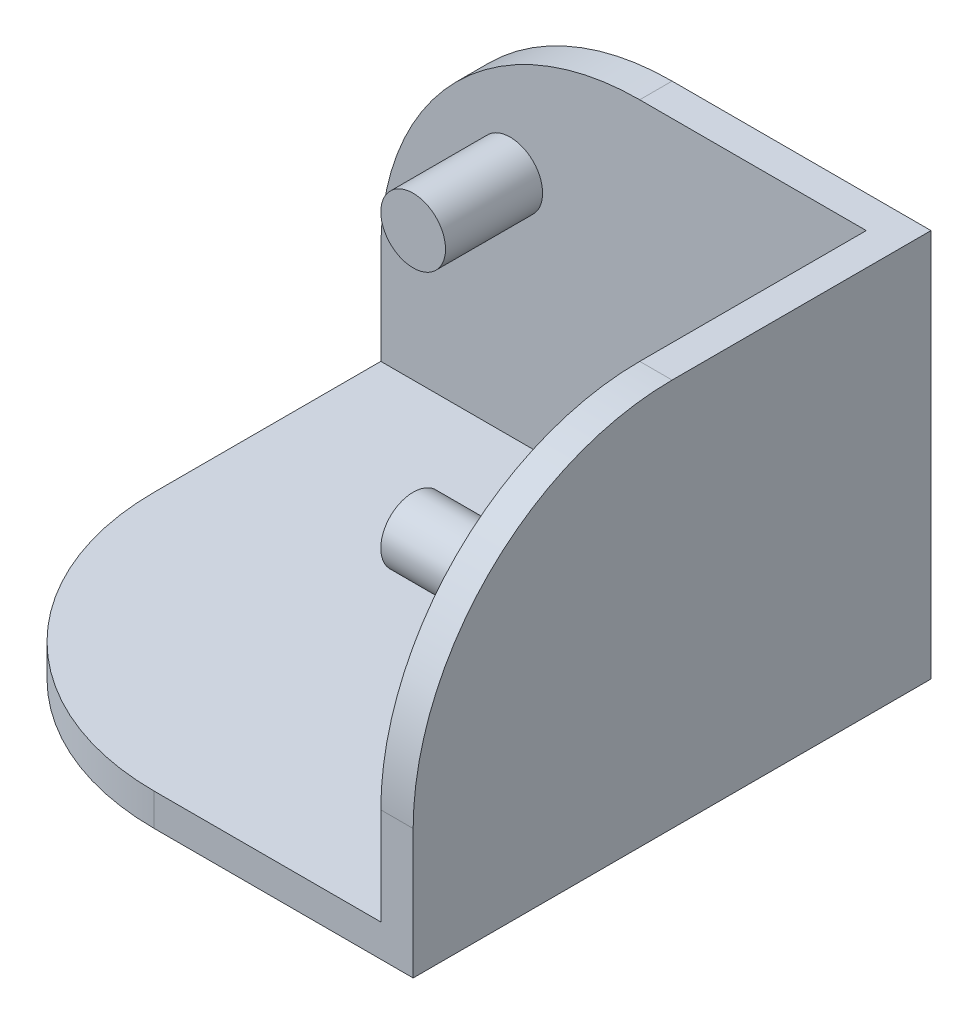
SolidWorks part; units mm, degrees
ref_plane "Front Plane" through (0, 0, 0) normal (0, 0, 1) x (1, 0, 0)
ref_plane "Top Plane" through (0, 0, 0) normal (0, 1, 0) x (1, 0, 0)
ref_plane "Right Plane" through (0, 0, 0) normal (1, 0, 0) x (0, 0, -1)
sketch "Sketch1" plane through (0, 0, 0) normal (0, 1, 0) x (1, 0, 0)
  line L1 (-40, 40) -> (40, 40)
  line L2 (-40, 40) -> (-40, -40)
  line L3 (-40, -40) -> (40, -40)
  line L4 (40, 40) -> (40, -40)
  line L5 (-40, 40) -> (40, -40) construction
  line L6 (-40, -40) -> (40, 40) construction
  point P0 (0, 0)
  dimension "D1" = 80
extrude "Boss-Extrude1" add sketch "Sketch1" along normal blind 5
sketch "Sketch3" plane through (0, 5, 0) normal (0, 1, 0) x (1, 0, 0)
  line L0 (-40, 40) -> (40, 40)
  line L1 (40, 40) -> (40, -40)
extrude "Extrude-Thin1" add sketch "Sketch3" along normal blind 55 thin
fillet "Fillet1" radius 40 3 edges at (-40, 60, -37.5) (37.5, 60, 40) (-40, 2.5, 40)
sketch "Sketch4" plane through (35, 0, 0) normal (-1, 0, 0) x (0, 0, 1)
  line L0 (40, 5) -> (0, 5) construction
  line L1 (-35, 20) -> (-35, 60) construction
  circle A0 centre (20, 40) radius 5
  point P3 (19.268, 39.4811)
  dimension "D1" = 10
  dimension "D2" = 35
  dimension "D3" = 55
extrude "Boss-Extrude2" add sketch "Sketch4" along normal blind 15
sketch "Sketch5" plane through (0, 0, -35) normal (0, 0, 1) x (1, 0, 0)
  line L1 (35, 60) -> (35, 20) construction
  line L2 (35, 45) -> (20, 45) construction
  line L3 (20, 35) -> (35, 35) construction
  circle A0 centre (-20, 40) radius 5
  point P3 (-19.3933, 40.5286)
  dimension "D1" = 55
extrude "Boss-Extrude3" add sketch "Sketch5" along normal blind 15
